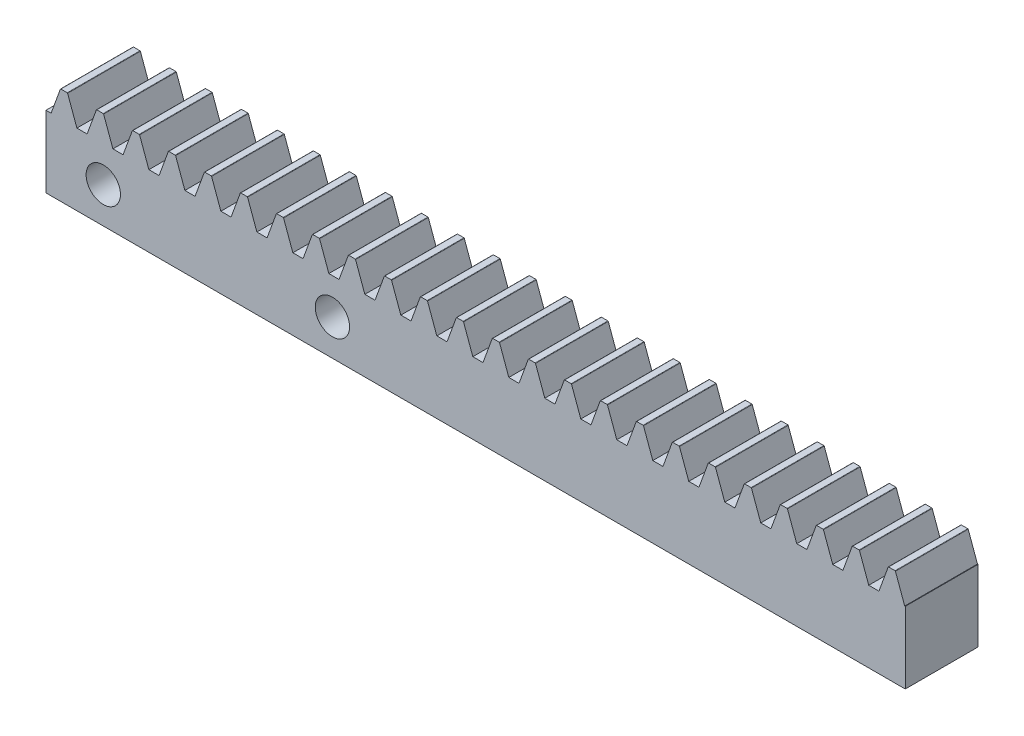
SolidWorks part; units mm, degrees
extrude "Blank" add sketch "BlankSke" against normal blind 6.35
sketch "BlankSke" plane through (0, 0, 0) normal (0, 0, 1) x (1, 0, 0)
  line L1 (0, 0) -> (75, 0)
  line L2 (0, 0) -> (0, 8.5)
  line L3 (0, 8.5) -> (75, 8.5)
  line L4 (75, 0) -> (75, 8.5)
  dimension "Length" = 75
  dimension "Blank_height" = 8.5
material "Custom Plastic"
ref_plane "Plane1" through (0, 0, 0) normal (0, 0, 1) x (1, 0, 0)
ref_plane "Plane2" through (0, 0, 0) normal (0, 1, 0) x (1, 0, 0)
ref_plane "Plane3" through (0, 0, 0) normal (1, 0, 0) x (0, 0, -1)
other "Configuration Table"
sketch "HoldingSke" plane through (0, 0, 0) normal (0, 1, 0) x (1, 0, 0)
  line L0 (0, 0) -> (-0.766, -0.6428)
  line L1 (-15, 0) -> (100, 0) construction
  line L2 (0, 0) -> (-2.1039, 2.3779)
  line L3 (0, 0) -> (-11.863, 4.5341)
  line L4 (0, 0) -> (7.8269, 3.6497)
  line L5 (0, 0) -> (-23.7986, -8.8762)
  line L6 (0, 0) -> (-10.5278, -7.1032)
  line L9 (-71.009, 38.7566) -> (-0.532, 64.4081)
  line L10 (-76.2, 3.3779) -> (-68.7, 3.3779)
  line L11 (0, 0) -> (-6.35, 0)
  line L12 (-76.2, 101.6) -> (-76.162, 101.6)
  line L13 (24.9733, 27.94) -> (52.9518, 28.4284)
  line L14 (24.9733, 27.94) -> (24.9743, 27.94)
  line L15 (24.9733, 27.94) -> (100.4006, 29.5858)
  circle A0 centre (0, 0) radius 19.05
  circle A1 centre (0, 0) radius 3.75
  circle A2 centre (0, 0) radius 12.7
  dimension "MPH" = 7.5
  dimension "Diameter" = 38.1
  dimension "Num_teeth" = 25
  dimension "Pitch" = 1
  dimension "Show_teeth" = 500
  dimension "Thickness" = 12.7
  dimension "Ap" = 20
  dimension "Pitch_height" = 7.5
  dimension "Width" = 6.35
  dimension "Backlash" = 0.038
  dimension "Addendum_fac" = 1
  dimension "Dedendum_fac" = 1.25
  dimension "Clearance_fac" = 0.25
  dimension "Dedendum_add" = 0.001
  dimension "Length" = 75
  dimension "Module" = 1
sketch "TooCutSkeIll" plane through (0, 0, 0) normal (0, 0, 1) x (1, 0, 0)
  line L0 (-1.2538, 8.4737) -> (-0.5045, 6.4152)
  line L1 (-0.2687, 6.25) -> (0.2687, 6.25)
  line L2 (0.5045, 6.4152) -> (1.2538, 8.4737)
  line L3 (75, 8.5) -> (0, 8.5) construction
  line L4 (0, 0) -> (0, 64.897) construction
  line L5 (-13.208, 7.5) -> (12.954, 7.5) construction
  line L6 (0, 0) -> (75, 0) construction
  line L7 (0.8994, 7.5) -> (0.8994, 48.7463) construction
  line L8 (-0.8994, 7.5) -> (-0.8994, 48.7463) construction
  line L9 (1.2914, 8.5) -> (1.2914, 8.5254)
  line L10 (-1.2914, 8.5) -> (-1.2914, 8.5254)
  line L11 (-1.2914, 8.5254) -> (1.2914, 8.5254)
  arc A0 (0.2687, 6.25) -> (0.5045, 6.4152) centre (0.2687, 6.501) ccw
  arc A1 (-0.5045, 6.4152) -> (-0.2687, 6.25) centre (-0.2687, 6.501) ccw
  arc A2 (1.2914, 8.5) -> (1.2538, 8.4737) centre (1.2914, 8.46) ccw
  arc A3 (-1.2538, 8.4737) -> (-1.2914, 8.5) centre (-1.2914, 8.46) ccw
  dimension "Pitch_height" = 7.5
  dimension "Addendum_plus" = 1.0254
  dimension "Pressure_angle" = 20
  dimension "Gap_width" = 1.7988
  dimension "Dedendum" = 1.25
extrude "ToothCutIll" cut sketch "TooCutSkeIll" against normal through all
sketch "TooCutSkeSim" plane through (0, 0, 0) normal (0, 0, 1) x (1, 0, 0)
  line L0 (0.4444, 6.25) -> (-0.4444, 6.25)
  line L1 (1.2726, 8.5254) -> (0.4444, 6.25)
  line L2 (0, 17.4625) -> (0, 53.467) construction
  line L3 (1.2726, 8.5254) -> (-1.2726, 8.5254)
  line L6 (-1.2726, 8.5254) -> (-0.4444, 6.25)
  line L9 (-0.8994, 7.5) -> (0.8994, 7.5) construction
  line L10 (0, 0) -> (75, 0) construction
  line L11 (0.8994, 7.5) -> (0.8994, 53.467) construction
  line L12 (-0.8994, 7.5) -> (-0.8994, 53.467) construction
  dimension "Pitch_height" = 7.5
  dimension "Addendum_plus" = 1.0254
  dimension "Pressure_angle" = 20
  dimension "Gap_width" = 1.7988
  dimension "Dedendum" = 1.25
extrude "ToothCutSim" cut sketch "TooCutSkeSim" against normal through all
pattern_linear "TeethCuts" count 24 spacing 3.1416 along (1, 0, 0) of "ToothCutIll", "ToothCutSim"
sketch "Sketch1" plane through (0, 0, 0) normal (0, 0, 1) x (1, 0, 0)
  line L0 (0, 3.125) -> (75, 3.125) construction
  line L1 (0, 6.25) -> (0, 0) construction
  line L2 (75, 0) -> (75, 6.25) construction
  circle A0 centre (5, 3.125) radius 1.5
  circle A1 centre (25, 3.125) radius 1.5
  dimension "D1" = 3
  dimension "D2" = 3
  dimension "D3" = 5
  dimension "D4" = 20
extrude "Cut-Extrude1" cut sketch "Sketch1" against normal up to surface (6.35 mm away) up to face at (37.6937, 7.6184, -6.35)
equation "' \"Module@HoldingSke\" = 6.35"
equation "' \"Num_teeth@HoldingSke\" = 12"
equation "' \"Ap@HoldingSke\" =  20"
equation "' \"Ap@HoldingSke\" = 20"
equation "' \"Width@HoldingSke\" = 0.25 * 25.4"
equation "' \"Show_teeth@HoldingSke\" = 500"
equation "' \"Backlash@HoldingSke\" = 0.009 * 25.4"
equation "' \"Addendum_fac@HoldingSke\" = 1.0"
equation "' \"Dedendum_fac@HoldingSke\" = 1.25"
equation "' \"Dedendum_add@HoldingSke\" = 0.00005 * 25.4"
equation "' \"Clearance_fac@HoldingSke\" = 0.25"
equation "' \"Pitch_height@HoldingSke\" = 1 * 25.4"
equation "' \"Length@HoldingSke\" = 4.71 * 25.4"
equation "\"Pitch@HoldingSke\" = 1 / \"Module@HoldingSke\""
equation "\"MPH@HoldingSke\" = \"Dedendum_fac@HoldingSke\" / \"Pitch@HoldingSke\" + 2 * \"Dedendum_add@HoldingSke\" + 0.002 * 25.4"
equation "\"MPH@HoldingSke\" = ((sgn( \"MPH@HoldingSke\" - \"Pitch_height@HoldingSke\")+1)*( \"MPH@HoldingSke\" - \"Pitch_height@HoldingSke\"))/2 + \"Pitch_height@HoldingSke\""
equation "\"Blank_height@BlankSke\" = \"Pitch_height@HoldingSke\" + \"Addendum_fac@HoldingSke\"  / \"Pitch@HoldingSke\" "
equation "\"Length@BlankSke\" =  \"Length@HoldingSke\""
equation "\"Face_width@Blank\" = \"Width@HoldingSke\""
equation "\"Pressure_angle@TooCutSkeIll\" = \"Ap@HoldingSke\""
equation "\"Addendum_plus@TooCutSkeIll\" =  \"Addendum_fac@HoldingSke\"  / \"Pitch@HoldingSke\" + 0.001 *25.4"
equation "\"Dedendum@TooCutSkeIll\" = \"Dedendum_fac@HoldingSke\"  / \"Pitch@HoldingSke\""
equation "\"Pitch_height@TooCutSkeIll\" =  \"MPH@HoldingSke\""
equation "\"Gap_width@TooCutSkeIll\" = 3.14159265 / 2 / \"Pitch@HoldingSke\" + 6 * \"Backlash@HoldingSke\""
equation "\"Pressure_angle@TooCutSkeSim\" = \"Ap@HoldingSke\""
equation "\"Addendum_plus@TooCutSkeSim\" =  \"Addendum_fac@HoldingSke\"  / \"Pitch@HoldingSke\" + 0.001 * 25.4"
equation "\"Dedendum@TooCutSkeSim\" = \"Dedendum_fac@HoldingSke\"  / \"Pitch@HoldingSke\""
equation "\"Pitch_height@TooCutSkeSim\" =  \"MPH@HoldingSke\""
equation "\"Gap_width@TooCutSkeSim\" = 3.14159265 / 2 / \"Pitch@HoldingSke\" + 6 * \"Backlash@HoldingSke\""
equation "\"Root_fillet@TooCutSkeIll\" = \"Clearance_fac@HoldingSke\" / \"Pitch@HoldingSke\" + \"Dedendum_add@HoldingSke\""
equation "\"Break_rad@TooCutSkeIll\" = 0.02 / \"Pitch@HoldingSke\" * 2"
equation "\"Linear_pitch@TeethCuts\" = 3.14159265 / \"Pitch@HoldingSke\""
equation "\"Num_teeth@HoldingSke\" = int( ( \"Length@HoldingSke\" + 0 ) / (3.14159265 / \"Pitch@HoldingSke\")) + 0.9999  + 1"
equation " \"Num_teeth@TeethCuts\" = int( \"Show_teeth@HoldingSke\" ) + 1"
equation " \"Num_teeth@TeethCuts\" = ((sgn( \"Num_teeth@TeethCuts\" - \"Num_teeth@HoldingSke\" )-1)*( \"Num_teeth@TeethCuts\" - \"Num_teeth@HoldingSke\" ))/-2+ \"Num_teeth@HoldingSke\""
equation " \"Num_teeth@TeethCuts\" = ((sgn( \"Num_teeth@TeethCuts\" - 2.0)+1)*( \"Num_teeth@TeethCuts\" - 2.0))/2 +2.0"
